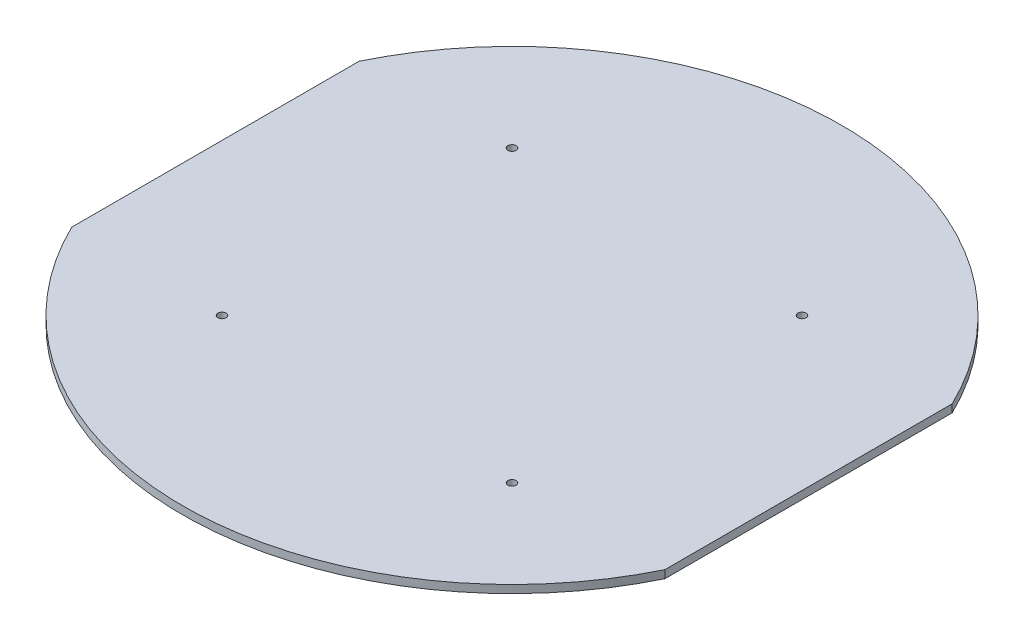
SolidWorks part; units mm, degrees
material "Acrylic (Medium-high impact)"
ref_plane "Front Plane" through (0, 0, 0) normal (0, 0, 1) x (1, 0, 0)
ref_plane "Top Plane" through (0, 0, 0) normal (0, 1, 0) x (1, 0, 0)
ref_plane "Right Plane" through (0, 0, 0) normal (1, 0, 0) x (0, 0, -1)
sketch "Sketch1" plane through (0, 0, 0) normal (0, 1, 0) x (1, 0, 0)
  line L0 (-112.5, 54.4862) -> (-112.5, -54.4862)
  line L7 (-55, 55) -> (55, 55) construction
  line L8 (-55, 55) -> (-55, -55) construction
  line L9 (-55, -55) -> (55, -55) construction
  line L10 (55, 55) -> (55, -55) construction
  line L11 (0, -55) -> (0, 55) construction
  line L12 (-55, 0) -> (55, 0) construction
  line L13 (112.5, 54.4862) -> (112.5, -54.4862)
  circle A0 centre (0, 0) radius 125
  circle A1 centre (-55, 55) radius 1.55
  circle A2 centre (55, 55) radius 1.55
  circle A3 centre (55, -55) radius 1.55
  circle A4 centre (-55, -55) radius 1.55
  point P3 (0, -111.9845)
  point P4 (0, 0)
  point P5 (-95.5436, 0)
  dimension "D5" = 250
  dimension "D7" = 3.1
  dimension "D1" = 112.5
  dimension "D3" = 110
  dimension "D4" = 110
  dimension "D8" = 2
  dimension "D9" = 2
extrude "Boss-Extrude1" add sketch "Sketch1" along normal blind 3
